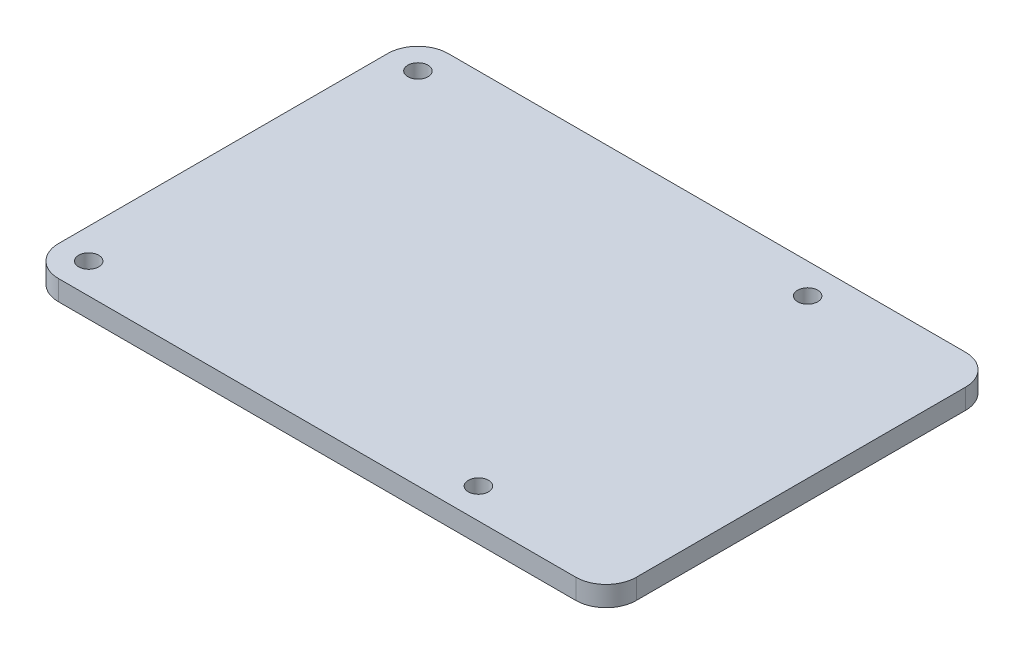
SolidWorks part; units mm, degrees
ref_plane "Front Plane" through (0, 0, 0) normal (0, 0, 1) x (1, 0, 0)
ref_plane "Top Plane" through (0, 0, 0) normal (0, 1, 0) x (1, 0, 0)
ref_plane "Right Plane" through (0, 0, 0) normal (1, 0, 0) x (0, 0, -1)
sketch "Sketch1" plane through (0, 0, 0) normal (0, 1, 0) x (1, 0, 0)
  line L6 (-42.0766, -7.7672) -> (-42.0766, 41.2328)
  line L8 (-37.5766, 45.7328) -> (39.4234, 45.7328)
  line L11 (-37.5766, -12.2672) -> (39.4234, -12.2672)
  line L13 (43.9234, 41.2328) -> (43.9234, -7.7672)
  circle A0 centre (-37.5766, 41.2328) radius 1.5
  circle A1 centre (20.4234, 41.2328) radius 1.5
  circle A2 centre (-37.5766, -7.7672) radius 1.5
  circle A3 centre (20.4234, -7.7672) radius 1.5
  arc A8 (-37.5766, 45.7328) -> (-42.0766, 41.2328) centre (-37.5766, 41.2328) ccw
  arc A10 (-42.0766, -7.7672) -> (-37.5766, -12.2672) centre (-37.5766, -7.7672) ccw
  arc A12 (43.9234, -7.7672) -> (39.4234, -12.2672) centre (39.4234, -7.7672) cw
  arc A13 (43.9234, 41.2328) -> (39.4234, 45.7328) centre (39.4234, 41.2328) ccw
  dimension "D1" = 4.5
extrude "Boss-Extrude1" add sketch "Sketch1" along normal blind 3
